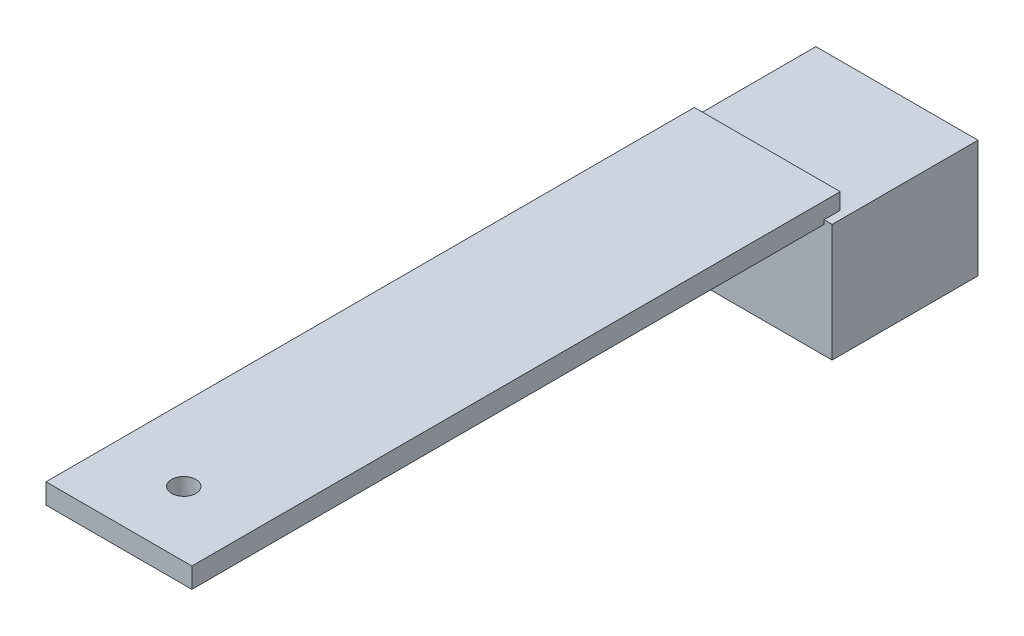
SolidWorks part; units mm, degrees
ref_plane "Front Plane" through (0, 0, 0) normal (0, 0, 1) x (1, 0, 0)
ref_plane "Top Plane" through (0, 0, 0) normal (0, 1, 0) x (1, 0, 0)
ref_plane "Right Plane" through (0, 0, 0) normal (1, 0, 0) x (0, 0, -1)
ref_plane "PZ_m72_000" through (0, 0, -72) normal (0, 0, 1) x (1, 0, 0)
sketch "S_box1" plane through (0, 0, -72) normal (0, 0, 1) x (1, 0, 0)
  line L0 (-9, 18.2) -> (9, 18.2)
  line L1 (9, 18.2) -> (9, 20.7)
  line L2 (9, 20.7) -> (-9, 20.7)
  line L3 (-9, 20.7) -> (-9, 18.2)
  dimension "P1" = 9
  dimension "P2" = 18.2
  dimension "P3" = 9
  dimension "P4" = 18.2
  dimension "P5" = 9
  dimension "P6" = 20.7
  dimension "P7" = 9
  dimension "P8" = 20.7
extrude "Boss_1" add sketch "S_box1" along normal blind 80
ref_plane "PZ_m88_000" through (0, 0, -88) normal (0, 0, 1) x (1, 0, 0)
sketch "S_box2" plane through (0, 0, -88) normal (0, 0, 1) x (1, 0, 0)
  line L0 (-10, 4.2) -> (10, 4.2)
  line L1 (10, 4.2) -> (10, 18.7)
  line L2 (10, 18.7) -> (-10, 18.7)
  line L3 (-10, 18.7) -> (-10, 4.2)
  dimension "P1" = 10
  dimension "P2" = 4.2
  dimension "P3" = 10
  dimension "P4" = 4.2
  dimension "P5" = 10
  dimension "P6" = 18.7
  dimension "P7" = 10
  dimension "P8" = 18.7
extrude "Boss_2" add sketch "S_box2" along normal blind 18
ref_plane "PY_p18_100" through (0, 18.1, 0) normal (0, 1, 0) x (1, 0, 0)
sketch "S_hole3" plane through (0, 18.1, 0) normal (0, 1, 0) x (1, 0, 0)
  circle A0 centre (0, 0) radius 1.5
  dimension "D1_S_hole3" = 3
extrude "Hole_3" cut sketch "S_hole3" along normal blind 2.7
equation "\"plate_t\" = 3"
equation "\"clearance\" = 0.4"
